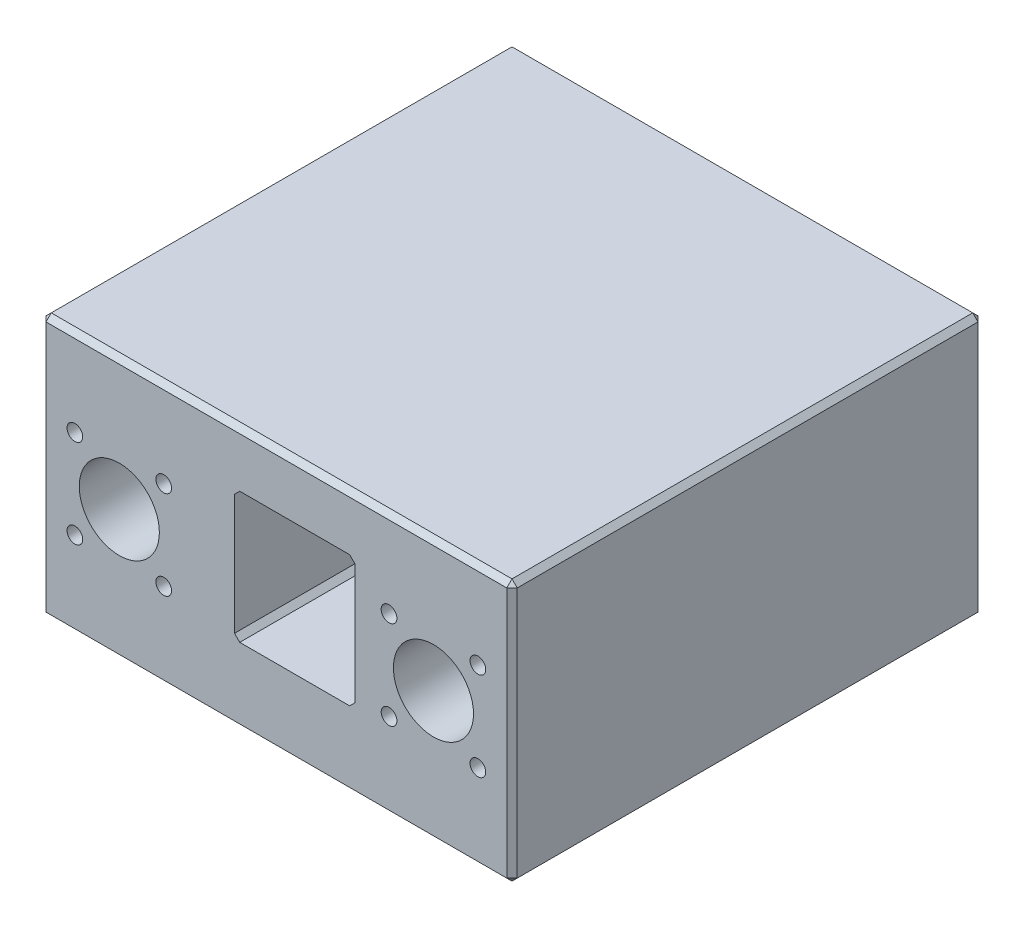
SolidWorks part; units mm, degrees
ref_plane "前视基准面" through (0, 0, 0) normal (0, 0, 1) x (1, 0, 0)
ref_plane "上视基准面" through (0, 0, 0) normal (0, 1, 0) x (1, 0, 0)
ref_plane "右视基准面" through (0, 0, 0) normal (1, 0, 0) x (0, 0, -1)
sketch "Sketch1" plane through (0, 0, 0) normal (0, 0, 1) x (1, 0, 0)
  line L1 (-45, 25) -> (45, 25)
  line L2 (-45, 25) -> (-45, -25)
  line L3 (-45, -25) -> (45, -25)
  line L4 (45, 25) -> (45, -25)
  line L5 (-45, 25) -> (45, -25) construction
  line L6 (-45, -25) -> (45, 25) construction
  point P0 (0, 0)
  dimension "D1" = 50
  dimension "D2" = 90
extrude "Boss-Extrude1" add sketch "Sketch1" along normal blind 90
sketch "Sketch2" plane through (0, 0, 90) normal (0, 0, 1) x (1, 0, 0)
  line L0 (0, 0) -> (0, 11.914) construction
  circle A0 centre (-30, 0) radius 7.65
  circle A1 centre (30, 0) radius 7.65
  dimension "D1" = 30
  dimension "D2" = 15.3
extrude "Cut-Extrude1" cut sketch "Sketch2" against normal through all
sketch "Sketch3" plane through (-45, 0, 0) normal (-1, 0, 0) x (0, 0, 1)
  line L0 (90, 25) -> (0, 25) construction
  line L1 (0, 25) -> (0, -25) construction
  line L2 (45, 25) -> (45, 34.6433) construction
  circle A0 centre (20, 20) radius 2.25
  circle A5 centre (70, 20) radius 2.25
  dimension "D1" = 4.5
  dimension "D2" = 5
  dimension "D3" = 20
extrude "Cut-Extrude2" cut sketch "Sketch3" against normal blind 10
sketch "Sketch4" plane through (0, -25, 0) normal (0, -1, 0) x (1, 0, 0)
  line L0 (-45, 90) -> (45, 90) construction
  line L1 (-45, 90) -> (-45, 0) construction
  line L2 (-45, 0) -> (45, 0) construction
  circle A3 centre (-38, 70) radius 1.5
  circle A4 centre (-38, 20) radius 1.5
  dimension "D1" = 3
  dimension "D3" = 20
  dimension "D4" = 7
  dimension "D5" = 3
  dimension "D2" = 20
extrude "Cut-Extrude3" cut sketch "Sketch4" against normal blind 10
sketch "Sketch5" plane through (0, 0, 90) normal (0, 0, 1) x (1, 0, 0)
  line L0 (-42, 0) -> (-30, 0) construction
  line L1 (-30, 0) -> (-38.4853, 8.4853) construction
  line L2 (0, 0) -> (0, 13.4381) construction
  line L3 (30, 0) -> (38.4853, 8.4853) construction
  line L4 (42, 0) -> (30, 0) construction
  circle A0 centre (-30, 0) radius 12 construction
  circle A1 centre (-38.4853, 8.4853) radius 1.5
  circle A2 centre (-21.5147, 8.4853) radius 1.5
  circle A3 centre (-21.5147, -8.4853) radius 1.5
  circle A4 centre (-38.4853, -8.4853) radius 1.5
  circle A5 centre (30, 0) radius 12 construction
  circle A6 centre (38.4853, -8.4853) radius 1.5
  circle A7 centre (21.5147, -8.4853) radius 1.5
  circle A8 centre (21.5147, 8.4853) radius 1.5
  circle A9 centre (38.4853, 8.4853) radius 1.5
  point P15 (-30, 0)
  dimension "D1" = 24
  dimension "D3" = 3
  dimension "D2" = 45
  dimension "D4" = 4
extrude "Cut-Extrude4" cut sketch "Sketch5" against normal through all
chamfer "Chamfer1" distance 1 angle 45 12 edges at (45, -25, 45) (45, 0, 90) (45, 0, 0) (45, 25, 45) (0, 25, 90) (-45, 25, 45) (0, 25, 0) (-45, 0, 0) (-45, 0, 90) (0, -25, 0) (-45, -25, 45) (0, -25, 90)
sketch "Sketch6" plane through (0, 0, 90) normal (0, 0, 1) x (1, 0, 0)
  line L1 (-8, 14.5) -> (15, 14.5)
  line L2 (-8, 14.5) -> (-8, -10.5)
  line L3 (-8, -10.5) -> (15, -10.5)
  line L4 (15, 14.5) -> (15, -10.5)
  point P0 (0, 2)
  point P5 (0, 0)
  dimension "D1" = 15
  dimension "D2" = 25
  dimension "D3" = 2
  dimension "D4" = 8
  dimension "D5" = 10.5
extrude "Cut-Extrude5" cut sketch "Sketch6" against normal through all
chamfer "Chamfer2" distance 1 angle 45 4 edges at (15, -10.5, 45) (15, 14.5, 45) (-8, 14.5, 45) (-8, -10.5, 45)
